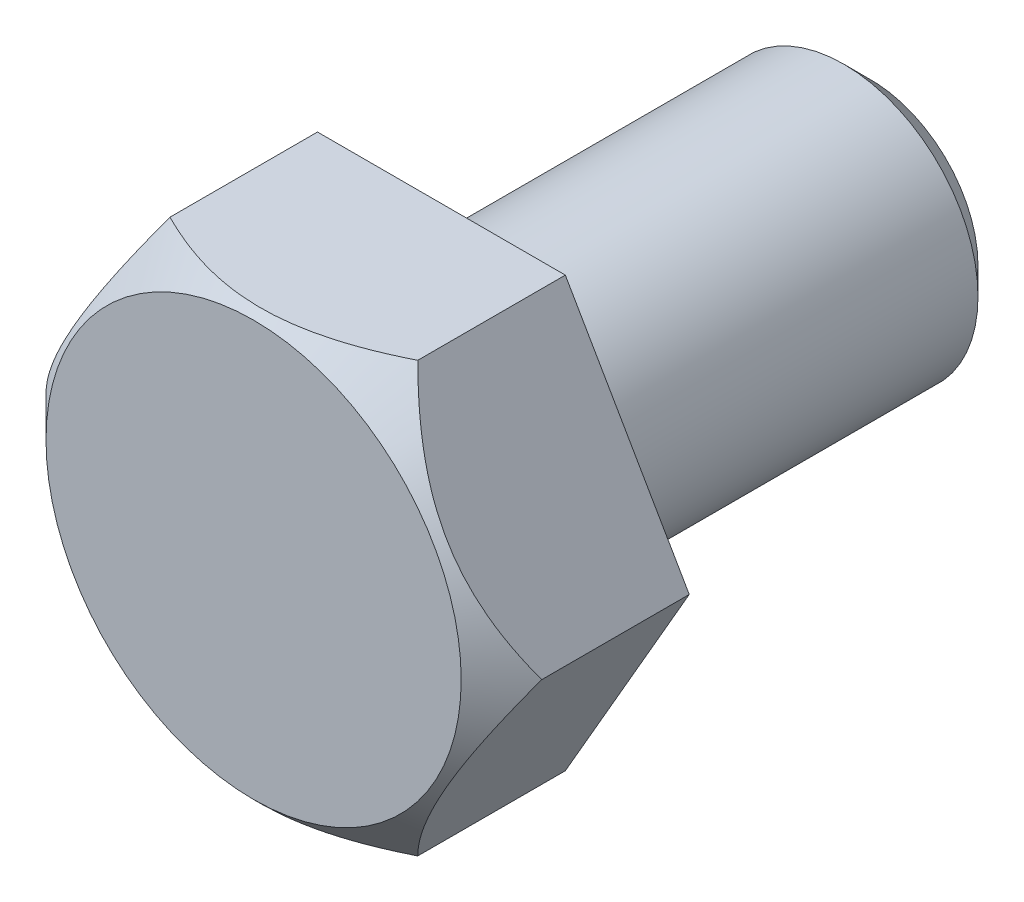
SolidWorks part; units mm, degrees
material "Plain Carbon Steel"
ref_plane "Front Plane" through (0, 0, 0) normal (0, 0, 1) x (1, 0, 0)
ref_plane "Top Plane" through (0, 0, 0) normal (0, 1, 0) x (1, 0, 0)
ref_plane "Right Plane" through (0, 0, 0) normal (1, 0, 0) x (0, 0, -1)
sketch "Sketch1" plane through (0, 0, 0) normal (0, 0, 1) x (1, 0, 0)
  line L1 (4.6188, 0) -> (2.3094, 4)
  line L2 (2.3094, 4) -> (-2.3094, 4)
  line L3 (-2.3094, 4) -> (-4.6188, 0)
  line L4 (-4.6188, 0) -> (-2.3094, -4)
  line L5 (-2.3094, -4) -> (2.3094, -4)
  line L6 (2.3094, -4) -> (4.6188, 0)
  circle A0 centre (0, 0) radius 4 construction
  dimension "D1" = 8
extrude "Boss-Extrude1" add sketch "Sketch1" along normal blind 3.5
sketch "Sketch3" plane through (0, 0, 0) normal (0, 0, -1) x (-1, 0, 0)
  circle A0 centre (0, 0) radius 3.25
  dimension "D1" = 6.5
extrude "Boss-Extrude3" add sketch "Sketch3" along normal blind 0.25
sketch "Sketch2" plane through (0, 0, 0) normal (0, 0, -1) x (-1, 0, 0)
  circle A0 centre (0, 0) radius 2.5
  dimension "D1" = 5
extrude "Boss-Extrude2" add sketch "Sketch2" along normal blind 8
cosmetic thread "Cosmetic Thread1" parameters "D2"=4.11
chamfer "Chamfer1" distance 0.5 angle 45 1 edges at (-2.5, 0, -8)
sketch "Sketch4" plane through (0, 0, 0) normal (0, 1, 0) x (1, 0, 0)
  line L0 (-4.8688, -3.75) -> (-4.8688, -2.5)
  line L2 (-3.6188, -3.75) -> (-4.8688, -3.75)
  line L3 (-4.6188, -3.5) -> (-4.6188, -2.75) construction
  line L4 (-4.6188, -3.5) -> (-4.6188, 0) construction
  line L5 (-4.6188, -3.5) -> (-3.8688, -3.5) construction
  line L6 (-3.8688, -3.5) -> (-4.6188, -2.75) construction
  line L7 (-3.6188, -3.75) -> (-4.8688, -2.5)
  line L8 (-4.6188, -3.5) -> (-4.8688, -3.75) construction
  line L9 (0, -3.5) -> (0, 8) construction
  line L10 (2.3094, -3.5) -> (-2.3094, -3.5) construction
  line L11 (2, 8) -> (-2, 8) construction
  dimension "D1" = 45
  dimension "D2" = 0.75
  dimension "D3" = 0.25
revolve "Cut-Revolve1" cut sketch "Sketch4" angle 360 about L9
equation "\"a\"= 1"
equation "\"b\"= 1"
equation "\"c\"= 1"
equation "\"d\"= 1"
equation "\"e\"= 1"
equation "\"x\"= 1"
equation "\"y\"= 1"
equation "\"z\"= 1"
